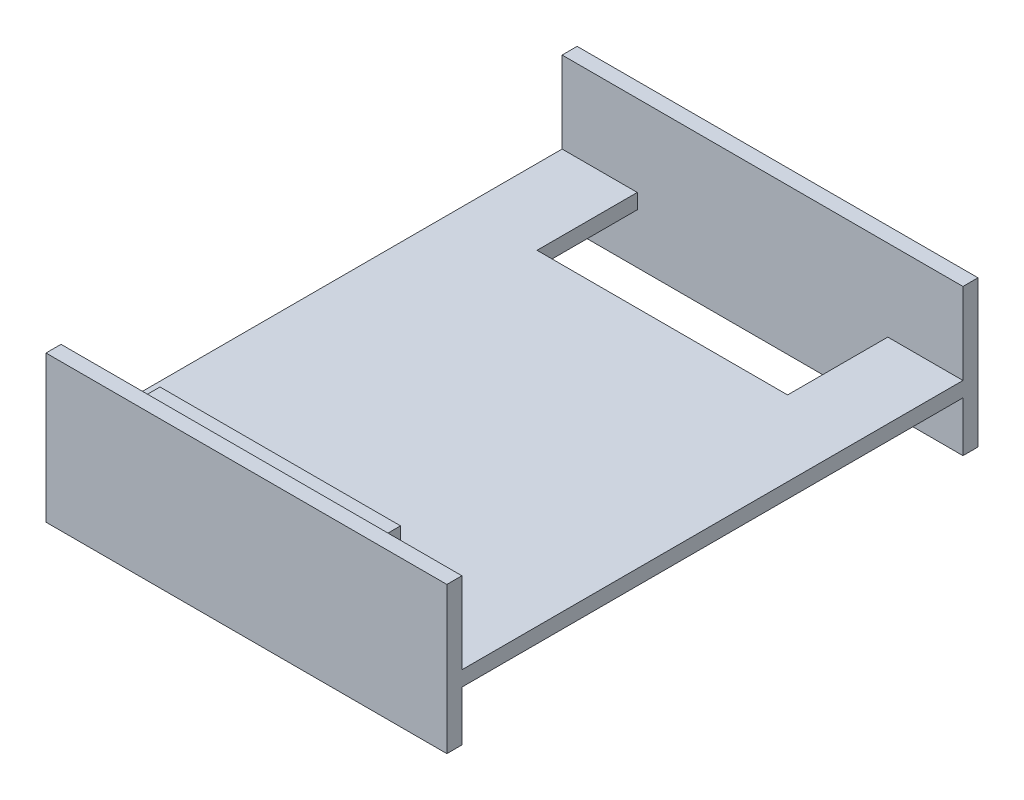
SolidWorks part; units mm, degrees
ref_plane "前视基准面" through (0, 0, 0) normal (0, 0, 1) x (1, 0, 0)
ref_plane "上视基准面" through (0, 0, 0) normal (0, 1, 0) x (1, 0, 0)
ref_plane "右视基准面" through (0, 0, 0) normal (1, 0, 0) x (0, 0, -1)
other "Configuration Table"
sketch "草图1" plane through (0, 0, 0) normal (0, 1, 0) x (1, 0, 0)
  line L1 (32, 0) -> (32, 40)
  line L3 (0, 40) -> (0, 0)
  line L4 (0, -1.2) -> (0, 0)
  line L5 (0, -1.2) -> (32, -1.2)
  line L6 (32, -1.2) -> (32, 0)
  line L7 (0, 40) -> (0, 41.2)
  line L8 (0, 41.2) -> (32, 41.2)
  line L9 (32, 41.2) -> (32, 40)
extrude "凸台-拉伸-中间层" add sketch "草图1" along normal blind 1.2
sketch "草图2" plane through (0, 1.2, 0) normal (0, 1, 0) x (1, 0, 0)
  line L0 (0, 0) -> (0, -1.2)
  line L1 (0, -1.2) -> (32, -1.2)
  line L2 (32, -1.2) -> (32, 0)
  line L3 (32, -1.2) -> (32, 41.2) construction
  line L4 (32, 0) -> (0, 0)
  line L5 (0, 41.2) -> (32, 41.2)
  line L6 (32, 41.2) -> (32, 40)
  line L7 (32, 40) -> (0, 40)
  line L8 (0, 41.2) -> (0, -1.2) construction
  line L9 (0, 40) -> (0, 41.2)
extrude "凸台-拉伸-PCB侧上下挡板" add sketch "草图2" along normal blind 6.5
sketch "草图3" plane through (0, 1.2, 0) normal (0, 1, 0) x (1, 0, 0)
  line L0 (32, 0) -> (0, 0) construction
  line L1 (16, 0) -> (25.6, 0)
  line L2 (32, 0) -> (0, 0) construction
  line L3 (25.6, 0) -> (25.6, 1.5)
  line L4 (16, 0) -> (6.4, 0)
  line L5 (6.4, 0) -> (6.4, 1.5)
  line L6 (6.4, 1.5) -> (25.6, 1.5)
  point P0 (16, 0)
extrude "凸台-拉伸-PCB侧下方卡槽" add sketch "草图3" along normal blind 6
sketch "草图4" plane through (0, 1.2, 0) normal (0, 1, 0) x (1, 0, 0)
  line L0 (0, 40) -> (32, 40) construction
  line L1 (16, 40) -> (26, 40)
  line L2 (0, 40) -> (32, 40) construction
  line L3 (16, 40) -> (6, 40)
  line L4 (6, 40) -> (6, 32)
  line L5 (6, 32) -> (26, 32)
  line L6 (26, 32) -> (26, 40)
  point P0 (16, 40)
extrude "切除-拉伸-穿线孔" cut sketch "草图4" against normal up to next
sketch "草图5" plane through (0, 0, 0) normal (0, -1, 0) x (1, 0, 0)
  line L0 (0, 1.2) -> (0, 0)
  line L1 (0, 0) -> (32, 0)
  line L3 (0, -40) -> (32, -40)
  line L5 (32, 0) -> (32, 1.2)
  line L6 (32, 1.2) -> (0, 1.2)
  line L7 (0, -40) -> (0, -41.2)
  line L8 (0, -41.2) -> (32, -41.2)
  line L9 (32, -41.2) -> (32, -40)
extrude "凸台-拉伸-电池侧上下挡板" add sketch "草图5" along normal blind 4
